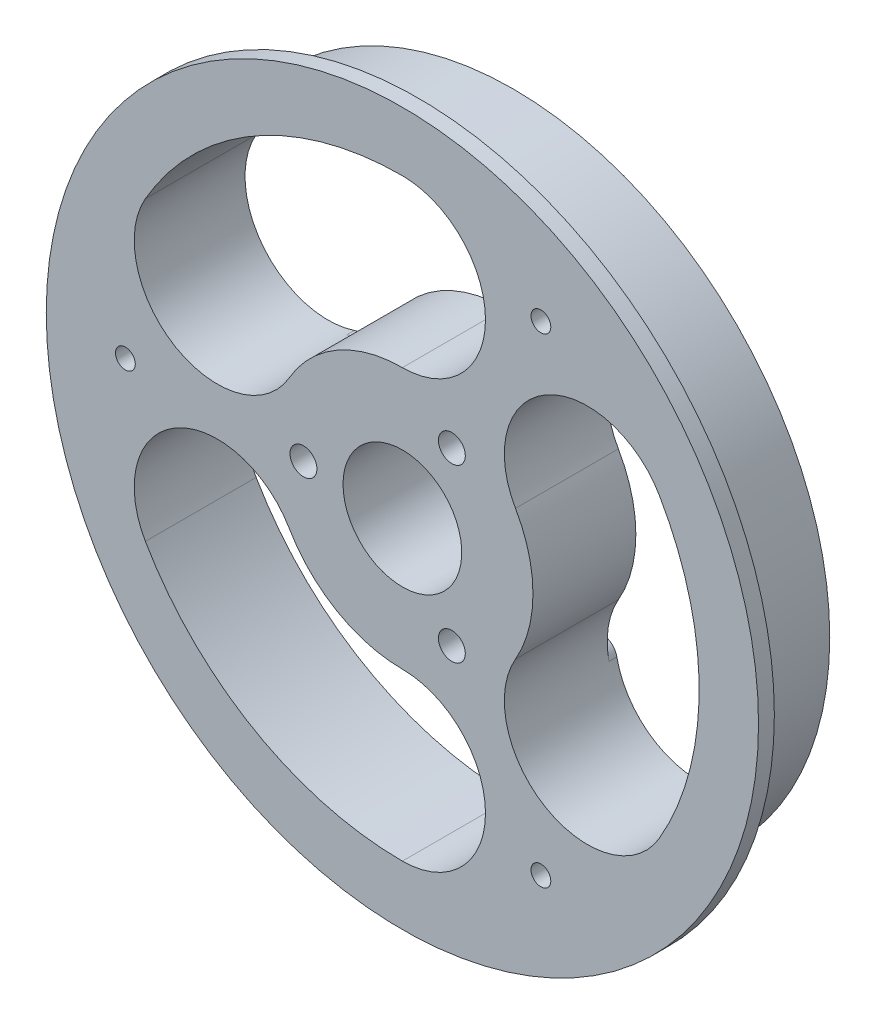
SolidWorks part; units mm, degrees
material "Сплав 2024"
ref_plane "Спереди" through (0, 0, 0) normal (0, 0, 1) x (1, 0, 0)
ref_plane "Сверху" through (0, 0, 0) normal (0, 1, 0) x (1, 0, 0)
ref_plane "Справа" through (0, 0, 0) normal (1, 0, 0) x (0, 0, -1)
sketch "Эскиз1" plane through (0, 0, 0) normal (0, 0, 1) x (1, 0, 0)
  circle A0 centre (0, 0) radius 40
  dimension "D1" = 80
extrude "Бобышка-Вытянуть1" add sketch "Эскиз1" along normal blind 12
sketch "Эскиз8" plane through (0, 0, 12) normal (0, 0, 1) x (1, 0, 0)
  circle A0 centre (0, 0) radius 45
  dimension "D1" = 90
extrude "Бобышка-Вытянуть3" add sketch "Эскиз8" along normal blind 2
sketch "Эскиз2" plane through (0, 0, 14) normal (0, 0, -1) x (-1, 0, 0)
  circle A0 centre (0, 0) radius 7.5
  dimension "D1" = 15
extrude "Вырез-Вытянуть1" cut sketch "Эскиз2" along normal through all
hole_wizard "Отверстие с зазором M31" positions "Эскиз4" profile "Эскиз3" hole size "M3" standard "Ansi Metric"
sketch "Эскиз4" plane through (-6.6635, -3.8899, 14) normal (0, 0, -1) x (-1, 0, 0)
  point P0 (20.5996, 37.0106)
sketch "Эскиз3" plane through (-27.2631, 33.1208, 14) normal (1, 0, 0) x (0, -1, 0)
  line L0 (0, 0) -> (0, 14)
  line L1 (0, 14) -> (1.7, 14)
  line L2 (1.7, 14) -> (1.7, 0)
  line L5 (1.7, 0) -> (0, 0)
  line L11 (0, -6.35) -> (0, 107.95) construction
  dimension "Диаметр сквозного отверстия" = 3.4
  dimension "Глубина сквозного отверстия" = 14
sketch "Эскиз10" plane through (0, 0, 0) normal (0, 0, -1) x (-1, 0, 0)
  line L1 (0, 49.276) -> (0, -49.5343) construction
  line L2 (46.4311, 26.807) -> (-46.4311, -26.807) construction
  arc A2 (32.476, -18.75) -> (14.2894, -8.25) centre (23.3827, -13.5) ccw
  arc A3 (32.476, 18.75) -> (0, 37.5) centre (0, 0) ccw
  circle A4 centre (0, 0) radius 27 construction
  arc A5 (0, 37.5) -> (0, 16.5) centre (0, 27) ccw
  arc A6 (14.2894, 8.25) -> (32.476, 18.75) centre (23.3827, 13.5) ccw
  arc A7 (14.2894, 8.25) -> (0, 16.5) centre (0, 0) ccw
  arc A8 (0, -16.5) -> (14.2894, -8.25) centre (0, 0) ccw
  arc A9 (0, -16.5) -> (0, -37.5) centre (0, -27) ccw
  arc A10 (0, -37.5) -> (32.476, -18.75) centre (0, 0) ccw
  arc A11 (-32.476, -18.75) -> (-14.2894, -8.25) centre (-23.3827, -13.5) ccw
  arc A12 (-14.2894, 8.25) -> (-14.2894, -8.25) centre (0, 0) ccw
  arc A13 (-14.2894, 8.25) -> (-32.476, 18.75) centre (-23.3827, 13.5) ccw
  arc A14 (-32.476, 18.75) -> (-32.476, -18.75) centre (0, 0) ccw
  point P28 (0, 0)
  dimension "D1" = 3
  dimension "D2" = 75
  dimension "D3" = 54
  dimension "D4" = 60
sketch "Эскиз11" plane through (0, 0, 14) normal (0, 0, 1) x (1, 0, 0)
  line L1 (6.25, 10.8253) -> (-6.25, -10.8253) construction
  line L2 (12.5, 0) -> (-12.5, 0) construction
  line L3 (-6.25, 10.8253) -> (6.25, -10.8253) construction
  circle A0 centre (0, 0) radius 12.5 construction
  dimension "D1" = 25
  dimension "D2" = 60
  dimension "D3" = 60
hole_wizard "Отверстие с зазором M32" positions "Эскиз13" profile "Эскиз12" hole size "M3" standard "Ansi Metric" end condition through all
sketch "Эскиз13" plane through (0, 0, 14) normal (0, 0, 1) x (1, 0, 0)
  point P0 (6.25, 10.8253)
  point P3 (-12.5, 0)
  point P9 (6.25, -10.8253)
sketch "Эскиз12" plane through (6.25, 10.8253, 14) normal (1, 0, 0) x (0, -1, 0)
  line L0 (0, 0) -> (0, 14)
  line L1 (0, 14) -> (1.7, 14)
  line L2 (1.7, 14) -> (1.7, 0)
  line L5 (1.7, 0) -> (0, 0)
  line L11 (0, -6.35) -> (0, 107.95) construction
  dimension "Диаметр сквозного отверстия" = 3.4
  dimension "Глубина сквозного отверстия" = 14
extrude "Вырез-Вытянуть2" cut sketch "Эскиз10" against normal through all
sketch "Эскиз14" plane through (0, 0, 0) normal (0, 0, -1) x (-1, 0, 0)
  line L2 (-55.8661, 0) -> (55.9948, 0) construction
  line L3 (-20, 34.641) -> (20, -34.641) construction
  line L4 (20, 34.641) -> (-20, -34.641) construction
  circle A0 centre (0, 0) radius 40 construction
  circle A1 centre (0, 0) radius 40 construction
  circle A2 centre (0, 0) radius 35 construction
  dimension "D3" = 70
  dimension "D1" = 60
  dimension "D2" = 60
hole_wizard "Отверстие обработанное метчиком M3x0.51" positions "Эскиз16" profile "Эскиз15" tap size "M3x0.5" standard "Ansi Metric" end condition through all
sketch "Эскиз16" plane through (0, 0, 0) normal (0, 0, -1) x (-1, 0, 0)
  line L0 (-20, 34.641) -> (20, -34.641) construction
  line L1 (20, 34.641) -> (-20, -34.641) construction
  line L2 (-55.8661, 0) -> (55.9948, 0) construction
  circle A0 centre (0, 0) radius 35 construction
  point P0 (-17.5, 30.3109)
  point P6 (35, 0)
  point P12 (-17.5, -30.3109)
sketch "Эскиз15" plane through (17.5, 30.3109, 0) normal (1, 0, 0) x (0, 1, 0)
  line L0 (0, 0) -> (0, 14)
  line L1 (0, 14) -> (1.25, 14)
  line L2 (1.25, 14) -> (1.25, 0)
  line L5 (1.25, 0) -> (0, 0)
  line L11 (0, -6.35) -> (0, 107.95) construction
  dimension "Диаметр проходного сверла" = 2.5
  dimension "Глубина проходного сверла" = 14
cosmetic thread "Отверстие резьбы4" parameters "D2"=3
cosmetic thread "Отверстие резьбы5" parameters "D2"=3
cosmetic thread "Отверстие резьбы6" parameters "D2"=3
sketch "Эскиз18" plane through (0, 0, 0) normal (0, 0, -1) x (-1, 0, 0)
  circle A0 centre (0, 0) radius 17.5
  dimension "D1" = 35
extrude "Вырез-Вытянуть4" cut sketch "Эскиз18" against normal blind 1
fillet "Скругление1" radius 2 6 edges at (-16.6253, 5.4633, 0.5) (-16.6253, -5.4633, 0.5) (3.5813, -17.1296, 0.5) (13.044, -11.6663, 0.5) (3.5813, 17.1296, 0.5) (13.044, 11.6663, 0.5)
